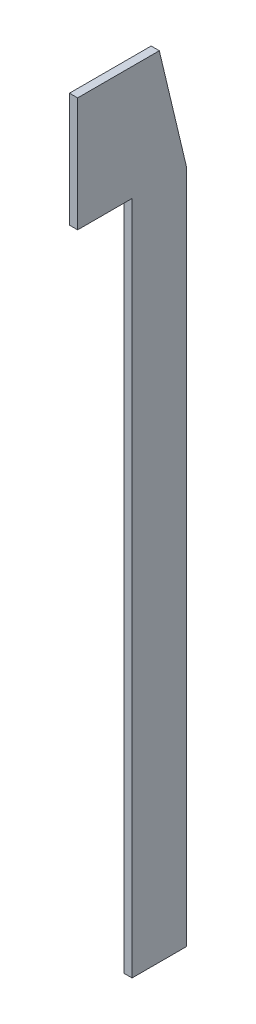
SolidWorks part; units mm, degrees
ref_plane "정면" through (0, 0, 0) normal (0, 0, 1) x (1, 0, 0)
ref_plane "윗면" through (0, 0, 0) normal (0, 1, 0) x (1, 0, 0)
ref_plane "우측면" through (0, 0, 0) normal (1, 0, 0) x (0, 0, -1)
sketch "스케치1" plane through (0, 0, 0) normal (1, 0, 0) x (0, 0, -1)
  line L1 (0, 0) -> (20, 0)
  line L2 (0, 0) -> (0, 248)
  line L4 (20, 0) -> (20, 290)
  line L5 (20, 290) -> (-20, 290)
  line L7 (0, 248) -> (-20, 248)
  line L8 (-20, 290) -> (-20, 248)
  dimension "D1" = 42
  dimension "D2" = 20
  dimension "D3" = 20
  dimension "D4" = 290
extrude "보스-돌출1" add sketch "스케치1" along normal blind 3
sketch "스케치2" plane through (3, 0, 0) normal (1, 0, 0) x (0, 0, -1)
  line L0 (10, 290) -> (20, 248)
  line L1 (20, 290) -> (-20, 290) construction
  line L2 (20, 0) -> (20, 290) construction
  line L3 (20, 248) -> (20, 290)
  line L4 (20, 290) -> (10, 290)
  line L5 (-20, 290) -> (-20, 248) construction
  dimension "D1" = 30
  dimension "D2" = 42
extrude "컷-돌출1" cut sketch "스케치2" against normal blind 3
